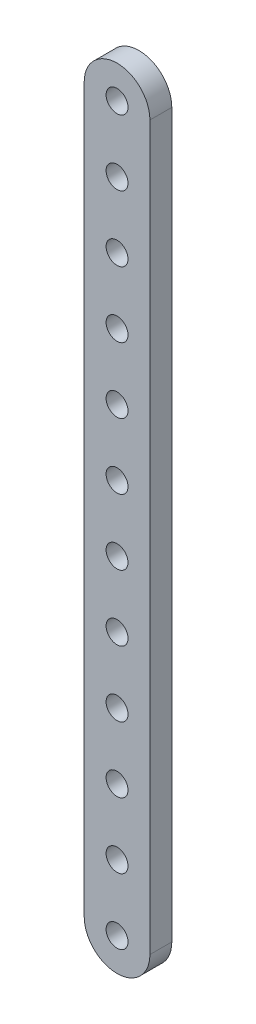
SolidWorks part; units mm, degrees
ref_plane "Alzado" through (0, 0, 0) normal (0, 0, 1) x (1, 0, 0)
ref_plane "Planta" through (0, 0, 0) normal (0, 1, 0) x (1, 0, 0)
ref_plane "Vista lateral" through (0, 0, 0) normal (1, 0, 0) x (0, 0, -1)
sketch "Model" plane through (0, 0, 0) normal (0, 0, 1) x (1, 0, 0)
  line L0 (213.2508, 89.4285) -> (213.2508, 188.4285)
  line L1 (204.2508, 188.4285) -> (204.2508, 89.4285)
  circle A0 centre (208.7508, 179.4285) radius 1.5
  circle A1 centre (208.7508, 188.4285) radius 1.5
  circle A2 centre (208.7508, 152.4285) radius 1.5
  circle A3 centre (208.7508, 161.4285) radius 1.5
  circle A4 centre (208.7508, 170.4285) radius 1.5
  arc A5 (204.2508, 89.4285) -> (213.2508, 89.4285) centre (208.7508, 89.4285) ccw
  arc A6 (213.2508, 188.4285) -> (204.2508, 188.4285) centre (208.7508, 188.4285) ccw
  circle A7 centre (208.7508, 143.4285) radius 1.5
  circle A8 centre (208.7508, 116.4285) radius 1.5
  circle A9 centre (208.7508, 125.4285) radius 1.5
  circle A10 centre (208.7508, 134.4285) radius 1.5
  circle A11 centre (208.7508, 89.4285) radius 1.5
  circle A12 centre (208.7508, 98.4285) radius 1.5
  circle A13 centre (208.7508, 107.4285) radius 1.5
extrude "Saliente-Extruir1" add sketch "Model" along normal blind 3
